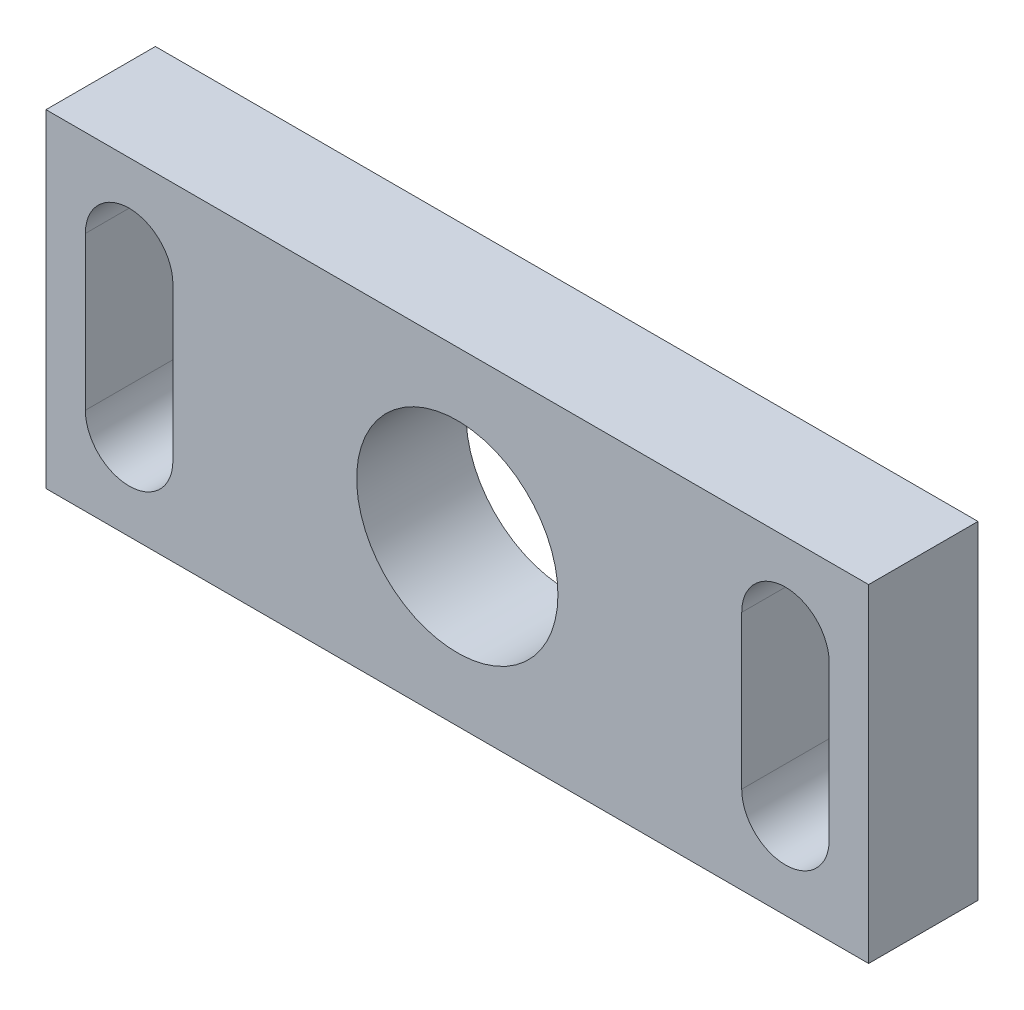
SolidWorks part; units mm, degrees
ref_plane "Front Plane" through (0, 0, 0) normal (0, 0, 1) x (1, 0, 0)
ref_plane "Top Plane" through (0, 0, 0) normal (0, 1, 0) x (1, 0, 0)
ref_plane "Right Plane" through (0, 0, 0) normal (1, 0, 0) x (0, 0, -1)
sketch "Sketch1" plane through (0, 0, 0) normal (0, 0, 1) x (1, 0, 0)
  line L1 (-18.8, 7.5) -> (18.8, 7.5)
  line L2 (-18.8, 7.5) -> (-18.8, -7.5)
  line L3 (-18.8, -7.5) -> (18.8, -7.5)
  line L4 (18.8, 7.5) -> (18.8, -7.5)
  line L5 (-18.8, 7.5) -> (18.8, -7.5) construction
  line L6 (-18.8, -7.5) -> (18.8, 7.5) construction
  point P0 (0, 0)
  dimension "D1" = 37.6
  dimension "D2" = 15
extrude "Boss-Extrude1" add sketch "Sketch1" along normal blind 5
sketch "Sketch2" plane through (0, 0, 5) normal (0, 0, 1) x (1, 0, 0)
  line L0 (-15, 3.5) -> (-15, -3.5) construction
  line L1 (-13, 3.5) -> (-13, -3.5)
  line L2 (-17, 3.5) -> (-17, -3.5)
  line L3 (15, 3.5) -> (15, -3.5) construction
  line L4 (17, 3.5) -> (17, -3.5)
  line L5 (13, 3.5) -> (13, -3.5)
  line L6 (-15, 0) -> (0, 0) construction
  line L7 (0, 0) -> (15, 0) construction
  arc A0 (-13, 3.5) -> (-17, 3.5) centre (-15, 3.5) ccw
  arc A1 (-17, -3.5) -> (-13, -3.5) centre (-15, -3.5) ccw
  arc A2 (17, 3.5) -> (13, 3.5) centre (15, 3.5) ccw
  arc A3 (13, -3.5) -> (17, -3.5) centre (15, -3.5) ccw
  point P2 (-15, 0)
  point P7 (15, 0)
  dimension "D1" = 2
  dimension "D2" = 15
  dimension "D3" = 7
extrude "Cut-Extrude1" cut sketch "Sketch2" against normal up to surface (5 mm away) up to face at (0, 0, 0)
sketch "Sketch3" plane through (0, 0, 5) normal (0, 0, 1) x (1, 0, 0)
  circle A0 centre (0, 0) radius 4.6
  dimension "D1" = 9.2
extrude "Cut-Extrude2" cut sketch "Sketch3" against normal up to surface (5 mm away) up to face at (-15, 0, 0)
